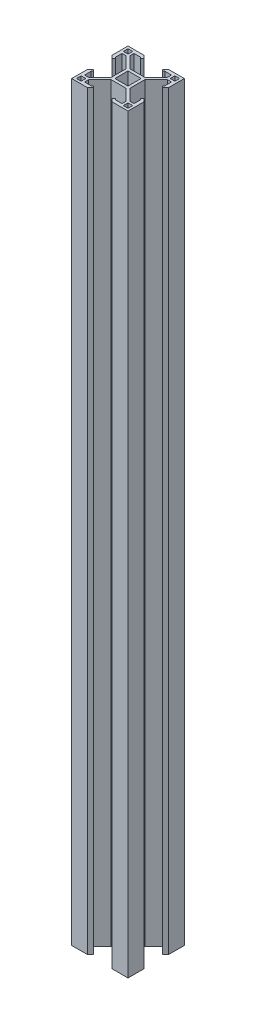
SolidWorks part; units mm, degrees
ref_plane "前视基准面" through (0, 0, 0) normal (0, 0, 1) x (1, 0, 0)
ref_plane "上视基准面" through (0, 0, 0) normal (0, 1, 0) x (1, 0, 0)
ref_plane "右视基准面" through (0, 0, 0) normal (1, 0, 0) x (0, 0, -1)
other "Configuration Table"
sketch "草图1" plane through (0, 0, 0) normal (0, 1, 0) x (1, 0, 0)
  line L1 (-15, 15) -> (15, 15)
  line L2 (-15, 15) -> (-15, -15)
  line L3 (-15, -15) -> (15, -15)
  line L4 (15, 15) -> (15, -15)
  line L5 (-15, 15) -> (15, -15) construction
  line L6 (-15, -15) -> (15, 15) construction
  point P0 (0, 0)
  dimension "D1" = 30
  dimension "D2" = 30
extrude "凸台-拉伸1" add sketch "草图1" along normal blind 400
sketch "草图2" plane through (0, 400, 0) normal (0, 1, 0) x (1, 0, 0)
  line L0 (0, 0) -> (0, 15) construction
  line L1 (15, 15) -> (-15, 15) construction
  line L2 (4.0046, 5) -> (9.9736, 10.969)
  line L3 (-5, -5) -> (5, -5)
  line L4 (-5, -5) -> (-5, 5)
  line L5 (-5, 5) -> (5, 5)
  line L6 (5, -5) -> (5, 5)
  line L7 (-5, -5) -> (5, 5) construction
  line L8 (-5, 5) -> (5, -5) construction
  line L9 (-9.9736, 10.969) -> (-9.9736, 13.1779)
  line L10 (-9.9736, 13.1779) -> (-6.4762, 13.1779)
  line L11 (-6.4762, 13.1779) -> (-5.8499, 12.5517)
  line L12 (-5.8499, 12.5517) -> (-5.0013, 13.4003)
  line L13 (-5.0013, 13.4003) -> (-6.601, 15)
  line L14 (10.969, 9.9736) -> (13.1779, 9.9736)
  line L15 (9.9736, 10.969) -> (9.9736, 13.1779)
  line L16 (9.9736, 13.1779) -> (6.4762, 13.1779)
  line L17 (6.4762, 13.1779) -> (5.8499, 12.5517)
  line L18 (5.8499, 12.5517) -> (5.0013, 13.4003)
  line L19 (5.0013, 13.4003) -> (6.601, 15)
  line L20 (-6.601, 15) -> (6.601, 15)
  line L21 (13.1779, 9.9736) -> (13.1779, 6.4762)
  line L22 (13.1779, 6.4762) -> (12.5517, 5.8499)
  line L23 (12.5517, 5.8499) -> (13.4003, 5.0013)
  line L24 (13.4003, 5.0013) -> (15, 6.601)
  line L25 (10.969, -9.9736) -> (13.1779, -9.9736)
  line L26 (13.1779, -9.9736) -> (13.1779, -6.4762)
  line L27 (13.1779, -6.4762) -> (12.5517, -5.8499)
  line L28 (12.5517, -5.8499) -> (13.4003, -5.0013)
  line L29 (13.4003, -5.0013) -> (15, -6.601)
  line L30 (15, 6.601) -> (15, -6.601)
  line L31 (5, -4.0046) -> (10.969, -9.9736)
  line L32 (5, 4.0046) -> (10.969, 9.9736)
  line L33 (9.9736, -10.969) -> (9.9736, -13.1779)
  line L34 (9.9736, -13.1779) -> (6.4762, -13.1779)
  line L35 (6.4762, -13.1779) -> (5.8499, -12.5517)
  line L36 (5.8499, -12.5517) -> (5.0013, -13.4003)
  line L37 (5.0013, -13.4003) -> (6.601, -15)
  line L38 (-9.9736, -10.969) -> (-9.9736, -13.1779)
  line L39 (-9.9736, -13.1779) -> (-6.4762, -13.1779)
  line L40 (-6.4762, -13.1779) -> (-5.8499, -12.5517)
  line L41 (-5.8499, -12.5517) -> (-5.0013, -13.4003)
  line L42 (-5.0013, -13.4003) -> (-6.601, -15)
  line L43 (6.601, -15) -> (-6.601, -15)
  line L44 (-4.0046, -5) -> (-9.9736, -10.969)
  line L45 (4.0046, -5) -> (9.9736, -10.969)
  line L46 (-10.969, -9.9736) -> (-13.1779, -9.9736)
  line L47 (-13.1779, -9.9736) -> (-13.1779, -6.4762)
  line L48 (-13.1779, -6.4762) -> (-12.5517, -5.8499)
  line L49 (-12.5517, -5.8499) -> (-13.4003, -5.0013)
  line L50 (-13.4003, -5.0013) -> (-15, -6.601)
  line L51 (-10.969, 9.9736) -> (-13.1779, 9.9736)
  line L52 (-13.1779, 9.9736) -> (-13.1779, 6.4762)
  line L53 (-13.1779, 6.4762) -> (-12.5517, 5.8499)
  line L54 (-12.5517, 5.8499) -> (-13.4003, 5.0013)
  line L55 (-13.4003, 5.0013) -> (-15, 6.601)
  line L56 (-15, -6.601) -> (-15, 6.601)
  line L57 (-5, 4.0046) -> (-10.969, 9.9736)
  line L58 (-5, -4.0046) -> (-10.969, -9.9736)
  line L59 (0, 0) -> (4.0046, 5) construction
  line L61 (-4.0046, 5) -> (-9.9736, 10.969)
  dimension "D1" = 10
  dimension "D2" = 10
  dimension "D3" = 4
  dimension "D4" = 6.406
extrude "切除-拉伸1" cut sketch "草图2" against normal blind 400
sketch "草图3" plane through (0, 400, 0) normal (0, 1, 0) x (1, 0, 0)
  line L0 (3.5, 3.5) -> (12.4868, 12.4868) construction
  line L1 (-3.5, 3.5) -> (3.5, 3.5)
  line L2 (-3.5, 3.5) -> (-3.5, -3.5)
  line L3 (-3.5, -3.5) -> (3.5, -3.5)
  line L4 (3.5, 3.5) -> (3.5, -3.5)
  line L5 (-3.5, 3.5) -> (3.5, -3.5) construction
  line L6 (-3.5, -3.5) -> (3.5, 3.5) construction
  line L7 (9.9736, 13.1779) -> (9.9736, 15) construction
  line L8 (15, 15) -> (6.601, 15) construction
  line L9 (9.9736, 15) -> (15, 15) construction
  line L10 (13.7368, -11.2368) -> (11.2368, -11.2368)
  line L11 (11.2368, 13.7368) -> (13.7368, 13.7368)
  line L12 (11.2368, 13.7368) -> (11.2368, 11.2368)
  line L13 (11.2368, 11.2368) -> (13.7368, 11.2368)
  line L14 (13.7368, 13.7368) -> (13.7368, 11.2368)
  line L15 (11.2368, 13.7368) -> (13.7368, 11.2368) construction
  line L16 (11.2368, 11.2368) -> (13.7368, 13.7368) construction
  line L17 (13.7368, -11.2368) -> (13.7368, -13.7368)
  line L18 (13.7368, -13.7368) -> (11.2368, -13.7368)
  line L19 (11.2368, -11.2368) -> (11.2368, -13.7368)
  line L20 (-11.2368, -13.7368) -> (-11.2368, -11.2368)
  line L21 (-11.2368, -13.7368) -> (-13.7368, -13.7368)
  line L22 (-13.7368, -13.7368) -> (-13.7368, -11.2368)
  line L23 (-11.2368, -11.2368) -> (-13.7368, -11.2368)
  line L24 (-13.7368, 11.2368) -> (-11.2368, 11.2368)
  line L25 (-13.7368, 11.2368) -> (-13.7368, 13.7368)
  line L26 (-13.7368, 13.7368) -> (-11.2368, 13.7368)
  line L27 (-11.2368, 11.2368) -> (-11.2368, 13.7368)
  line L28 (0, 0) -> (11.2368, 11.2368) construction
  point P0 (0, 0)
  point P15 (12.4868, 15)
  dimension "D1" = 7
  dimension "D2" = 7
  dimension "D3" = 135
  dimension "D4" = 2.5
  dimension "D5" = 2.5
  dimension "D7" = 15.8913
  dimension "D6" = 4
extrude "切除-拉伸2" cut sketch "草图3" against normal blind 400
